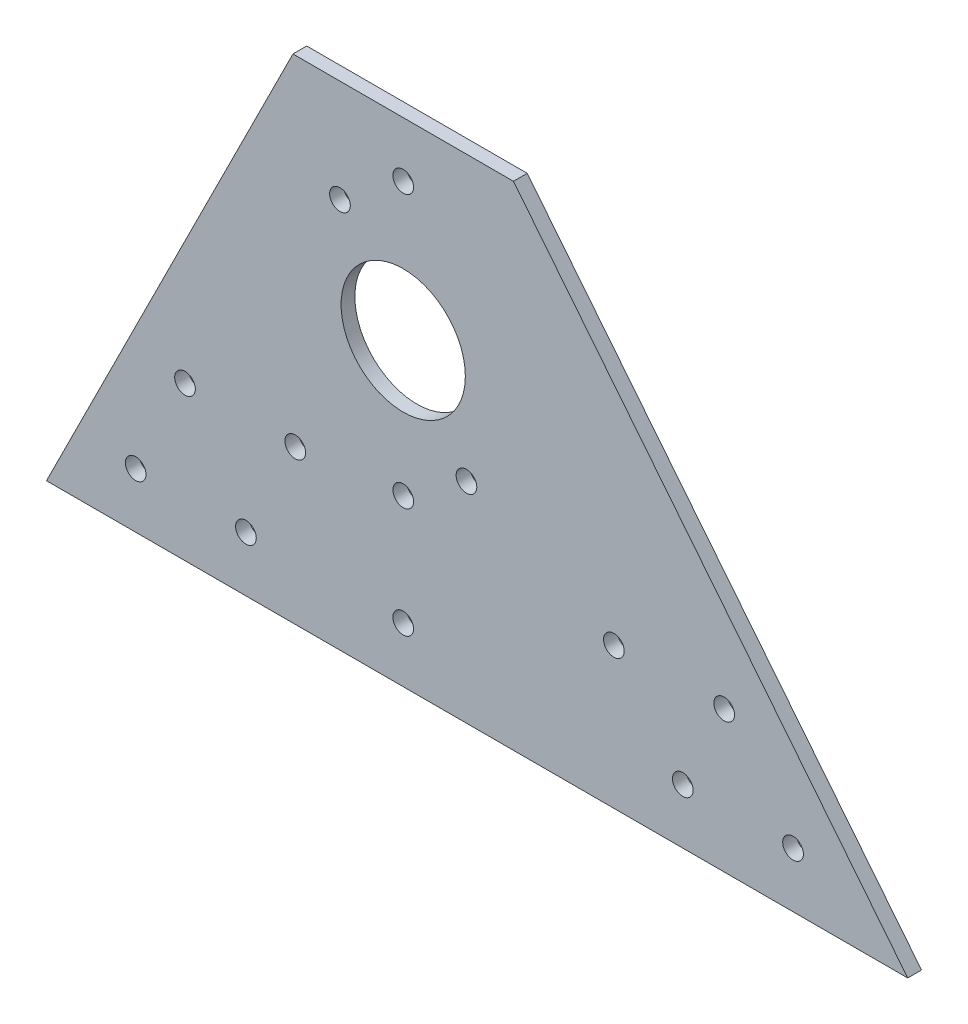
SolidWorks part; units mm, degrees
material "6063-T1"
ref_plane "Front Plane" through (0, 0, 0) normal (0, 0, 1) x (1, 0, 0)
ref_plane "Top Plane" through (0, 0, 0) normal (0, 1, 0) x (1, 0, 0)
ref_plane "Right Plane" through (0, 0, 0) normal (1, 0, 0) x (0, 0, -1)
sketch "Sketch1" plane through (0, 0, 0) normal (0, 0, 1) x (1, 0, 0)
  line L0 (25.4, 56.769) -> (116.231, -56.769)
  line L1 (-25.4, 56.769) -> (25.4, 56.769)
  line L2 (-25.4, 56.769) -> (-25.4, -56.769)
  line L3 (-25.4, -56.769) -> (25.4, -56.769)
  line L4 (25.4, 56.769) -> (25.4, -56.769)
  line L5 (-25.4, 56.769) -> (25.4, -56.769) construction
  line L6 (-25.4, -56.769) -> (25.4, 56.769) construction
  line L7 (116.231, -56.769) -> (25.4, -56.769)
  line L8 (-25.4, 56.769) -> (-82.1813, -56.769)
  line L9 (-82.1813, -56.769) -> (-25.4, -56.769)
  circle A0 centre (0, 12.319) radius 14.3129
  point P0 (0, 0)
  dimension "D3" = 28.6258
  dimension "D1" = 38.66
  dimension "D2" = 26.57
  dimension "D4" = 50.8
  dimension "D5" = 44.45
  dimension "D6" = 113.538
extrude "Boss-Extrude1" add sketch "Sketch1" along normal blind 3.175 contours L8 L9 L2 | L4 L1 L2 L3 A0 | L7 L0 L4
sketch "Sketch2" plane through (0, 0, 3.175) normal (0, 0, 1) x (1, 0, 0)
  line L0 (-82.1813, -56.769) -> (116.231, -56.769) construction
  line L1 (-25.4, 56.769) -> (-82.1813, -56.769) construction
  line L2 (25.4, 56.769) -> (116.231, -56.769) construction
  circle A0 centre (-61.6302, -44.069) radius 2.3812
  circle A1 centre (-36.2302, -44.069) radius 2.3812
  circle A3 centre (-50.2691, -21.3515) radius 2.3813
  circle A4 centre (-24.8691, -21.3515) radius 2.3812
  circle A5 centre (64.407, -44.069) radius 2.3813
  circle A6 centre (89.807, -44.069) radius 2.3813
  circle A7 centre (48.5397, -24.235) radius 2.3813
  circle A8 centre (73.9397, -24.235) radius 2.3813
  dimension "D1" = 4.7625
  dimension "D2" = 4.7625
  dimension "D7" = 4.7625
  dimension "D8" = 4.7625
  dimension "D3" = 12.7
  dimension "D4" = 12.7
  dimension "D5" = 25.4
  dimension "D9" = 12.7
  dimension "D10" = 12.7
  dimension "D11" = 25.4
  dimension "D6" = 2
  dimension "D12" = 2
extrude "Cut-Extrude1" cut sketch "Sketch2" against normal through all
sketch "Sketch3" plane through (0, 0, 3.175) normal (0, 0, 1) x (1, 0, 0)
  line L0 (-25.4, 56.769) -> (25.4, 56.769) construction
  line L1 (-82.1813, -56.769) -> (116.231, -56.769) construction
  circle A0 centre (0, 44.069) radius 2.3812
  circle A1 centre (0, -18.669) radius 2.3813
  circle A2 centre (0, -44.069) radius 2.3812
  dimension "D1" = 4.7625
  dimension "D2" = 4.7625
  dimension "D3" = 4.7625
  dimension "D4" = 12.7
  dimension "D5" = 12.7
  dimension "D6" = 25.4
extrude "Cut-Extrude2" cut sketch "Sketch3" against normal through all
sketch "Sketch4" plane through (0, 0, 3.175) normal (0, 0, 1) x (1, 0, 0)
  line L0 (0, 56.769) -> (0, -56.769) construction
  line L1 (-25.4, 56.769) -> (25.4, 56.769) construction
  line L2 (-82.1813, -56.769) -> (116.231, -56.769) construction
  line L3 (-14.5688, 33.1255) -> (14.5688, -8.4875) construction
  circle A0 centre (-14.5688, 33.1255) radius 2.3813
  circle A1 centre (0, 12.319) radius 25.4 construction
  circle A2 centre (14.5688, -8.4875) radius 2.3813
  dimension "D1" = 50.8
  dimension "D2" = 4.7625
  dimension "D4" = 4.7625
  dimension "D3" = 35
extrude "Cut-Extrude3" cut sketch "Sketch4" against normal through all
